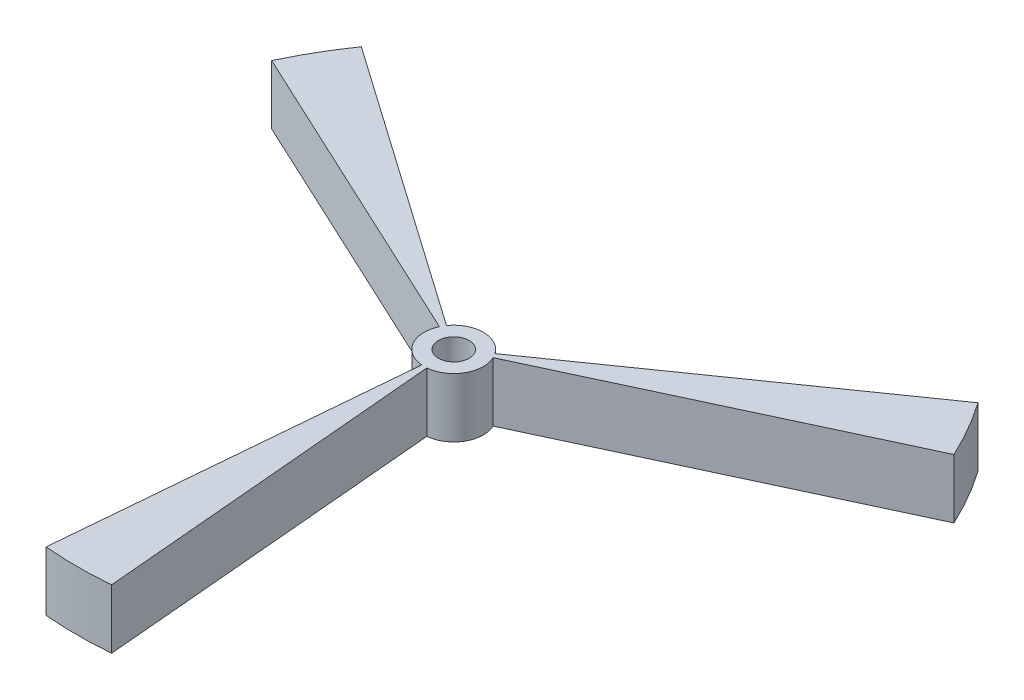
SolidWorks part; units mm, degrees
material "PE High Density"
ref_plane "Front Plane" through (0, 0, 0) normal (0, 0, 1) x (1, 0, 0)
ref_plane "Top Plane" through (0, 0, 0) normal (0, 1, 0) x (1, 0, 0)
ref_plane "Right Plane" through (0, 0, 0) normal (1, 0, 0) x (0, 0, -1)
sketch "Sketch1" plane through (0, 0, 0) normal (0, 1, 0) x (1, 0, 0)
  circle A0 centre (0, 0) radius 63.5
  circle A1 centre (0, 0) radius 2.6
  dimension "D1" = 127
  dimension "D2" = 5.2
extrude "Boss-Extrude1" add sketch "Sketch1" along normal blind 10
sketch "Sketch2" plane through (0, 10, 0) normal (0, 1, 0) x (1, 0, 0)
  line L0 (0, 0) -> (5.5344, -63.2584)
  line L1 (0, 0) -> (-5.5344, -63.2584)
  line L2 (0, 0) -> (0, -10.7097) construction
  line L3 (0, 0) -> (-15.5952, 9.0039) construction
  line L4 (0, 0) -> (21.4798, 12.4014) construction
  line L5 (0, 0) -> (-57.5505, 26.8363)
  line L6 (0, 0) -> (-52.0162, 36.4221)
  line L7 (0, 0) -> (52.0162, 36.4221)
  line L8 (0, 0) -> (57.5505, 26.8363)
  circle A0 centre (0, 0) radius 5
  circle A1 centre (0, 0) radius 63.5 construction
  arc A2 (57.5505, 26.8363) -> (5.5344, -63.2584) centre (0, 0) cw
  arc A3 (-5.5344, -63.2584) -> (-57.5505, 26.8363) centre (0, 0) cw
  arc A4 (-52.0162, 36.4221) -> (52.0162, 36.4221) centre (0, 0) cw
  dimension "D9" = 10
  dimension "D1" = 120
  dimension "D2" = 120
  dimension "D3" = 5
  dimension "D4" = 5
  dimension "D5" = 5
  dimension "D6" = 5
  dimension "D7" = 5
  dimension "D8" = 5
extrude "Cut-Extrude1" cut sketch "Sketch2" against normal blind 10 contours A0 L0 L8 | A0 L5 L1 | A0 L7 L6
